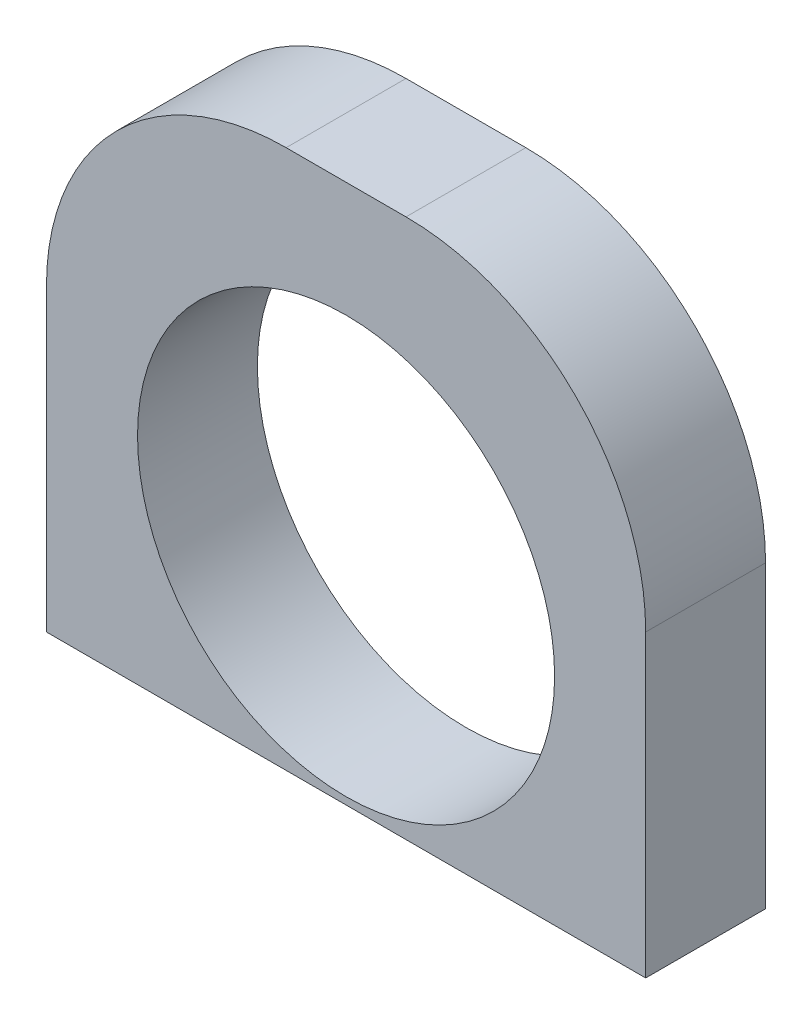
SolidWorks part; units mm, degrees
ref_plane "Front Plane" through (0, 0, 0) normal (0, 0, 1) x (1, 0, 0)
ref_plane "Top Plane" through (0, 0, 0) normal (0, 1, 0) x (1, 0, 0)
ref_plane "Right Plane" through (0, 0, 0) normal (1, 0, 0) x (0, 0, -1)
sketch "Sketch1" plane through (0, 0, 0) normal (0, 0, 1) x (1, 0, 0)
  line L4 (-15.875, -14.2875) -> (15.875, -14.2875)
  line L5 (-15.875, -14.2875) -> (-15.875, 1.5875)
  line L6 (-3.175, 14.2875) -> (3.175, 14.2875)
  line L7 (15.875, -14.2875) -> (15.875, 1.5875)
  line L8 (-15.875, -14.2875) -> (15.875, 14.2875) construction
  line L9 (-15.875, 14.2875) -> (15.875, -14.2875) construction
  circle A1 centre (0, -2.8575) radius 11.049
  arc A2 (3.175, 14.2875) -> (15.875, 1.5875) centre (3.175, 1.5875) cw
  arc A3 (-15.875, 1.5875) -> (-3.175, 14.2875) centre (-3.175, 1.5875) cw
  point P0 (0, 0)
  point P4 (0, 0)
  dimension "D1" = 31.75
  dimension "D3" = 22.098
  dimension "D4" = 12.7
  dimension "D2" = 28.575
  dimension "D5" = 11.43
extrude "Boss-Extrude3" add sketch "Sketch1" along normal blind 6.35
